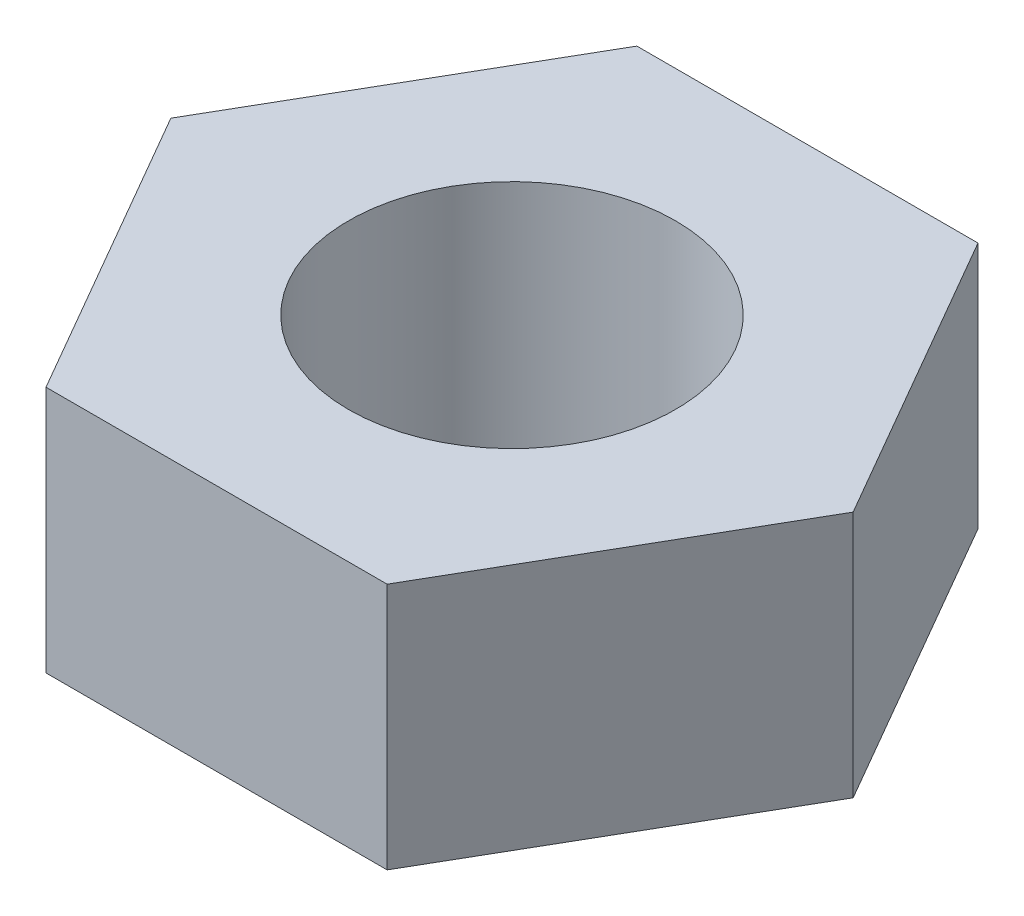
SolidWorks part; units mm, degrees
ref_plane "Front Plane" through (0, 0, 0) normal (0, 0, 1) x (1, 0, 0)
ref_plane "Top Plane" through (0, 0, 0) normal (0, 1, 0) x (1, 0, 0)
ref_plane "Right Plane" through (0, 0, 0) normal (1, 0, 0) x (0, 0, -1)
sketch "Sketch1" plane through (0, 0, 0) normal (0, 1, 0) x (1, 0, 0)
  line L1 (3.1292, 0) -> (1.5646, 2.71)
  line L2 (1.5646, 2.71) -> (-1.5646, 2.71)
  line L3 (-1.5646, 2.71) -> (-3.1292, 0)
  line L4 (-3.1292, 0) -> (-1.5646, -2.71)
  line L5 (-1.5646, -2.71) -> (1.5646, -2.71)
  line L6 (1.5646, -2.71) -> (3.1292, 0)
  circle A0 centre (0, 0) radius 2.71 construction
extrude "Boss-Extrude1" add sketch "Sketch1" along normal blind 2.27
sketch "Sketch2" plane through (0, 2.27, 0) normal (0, 1, 0) x (1, 0, 0)
  circle A0 centre (0, 0) radius 1.5
extrude "Cut-Extrude1" cut sketch "Sketch2" against normal blind 2.27
